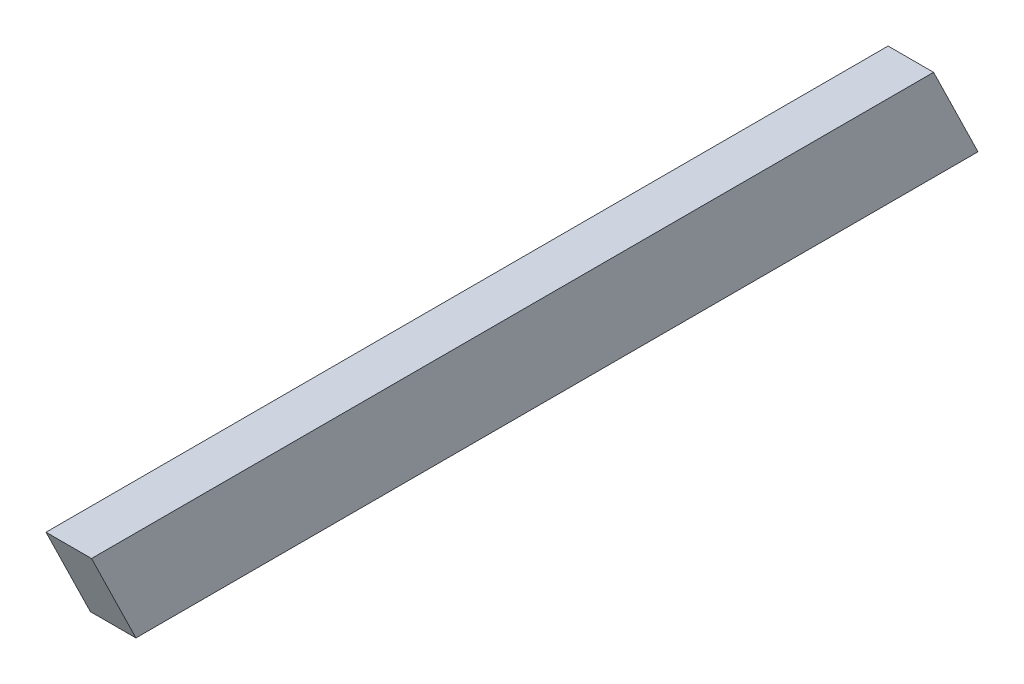
SolidWorks part; units mm, degrees
ref_plane "Front" through (0, 0, 0) normal (0, 0, 1) x (1, 0, 0)
ref_plane "Top" through (0, 0, 0) normal (0, 1, 0) x (1, 0, 0)
ref_plane "Right" through (0, 0, 0) normal (1, 0, 0) x (0, 0, -1)
sketch "Эскиз1" plane through (0, 0, 0) normal (1, 0, 0) x (0, 0, -1)
  line L0 (-472.4226, -114.7952) -> (-452.9133, -154.7952)
  line L1 (-102.4226, -114.7952) -> (-472.4226, -114.7952)
  line L3 (-82.9133, -154.7952) -> (-452.9133, -154.7952)
  line L5 (-82.9133, -154.7952) -> (-102.4226, -114.7952)
  dimension "D1" = 40
  dimension "D2" = 64
  dimension "D3" = 370
extrude "Бобышка-Вытянуть1" add sketch "Эскиз1" along normal blind 20
